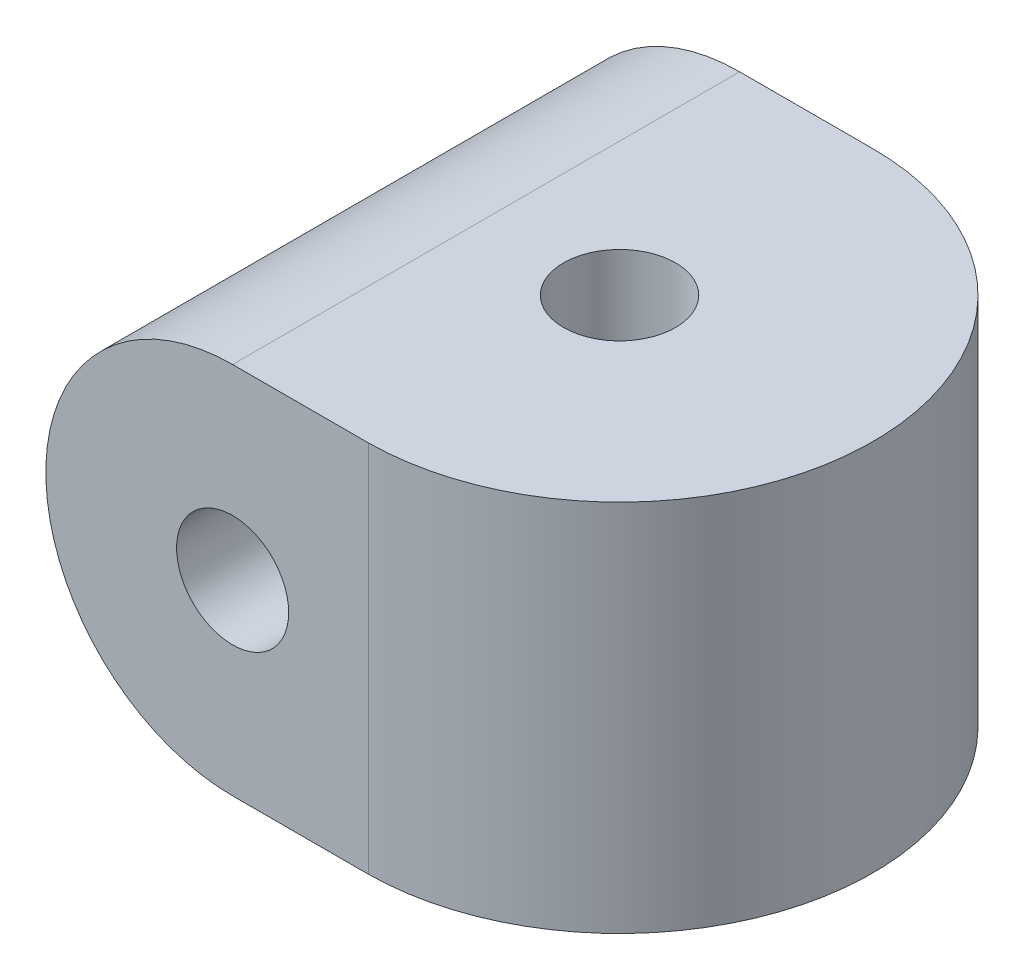
SolidWorks part; units mm, degrees
ref_plane "Alzado" through (0, 0, 0) normal (0, 0, 1) x (1, 0, 0)
ref_plane "Planta" through (0, 0, 0) normal (0, 1, 0) x (1, 0, 0)
ref_plane "Vista lateral" through (0, 0, 0) normal (1, 0, 0) x (0, 0, -1)
sketch "Croquis1" plane through (0, 0, 0) normal (0, 1, 0) x (1, 0, 0)
  line L0 (0, 9.5) -> (-15, 9.5)
  line L1 (-15, 9.5) -> (-15, -9.4996)
  line L2 (-15, -9.4996) -> (0.0848, -9.4996)
  line L3 (0, 0) -> (0, 50000) construction
  line L4 (-5, -17.8118) -> (-5, 49982.1882) construction
  circle A0 centre (0, 0) radius 9.5 construction
  circle A1 centre (0, 0) radius 2.1
  arc A2 (0, 9.5) -> (0.0848, -9.4996) centre (0, 0) cw
  dimension "D1" = 4.2
  dimension "D2" = 19
  dimension "D3" = 5
  dimension "D4" = 10
extrude "Saliente-Extruir1" add sketch "Croquis1" along normal mid plane 14
sketch "Croquis2" plane through (0, 0, 9.4996) normal (0, 0, 1) x (1, 0, 0)
  line L0 (0, 0) -> (-15, 0) construction
  circle A0 centre (-5, 0) radius 2.1
  dimension "D1" = 5
  dimension "D2" = 4.2
extrude "Cortar-Extruir1" cut sketch "Croquis2" against normal through all
sketch "Croquis3" plane through (0, 0, 9.4996) normal (0, 0, 1) x (1, 0, 0)
  line L0 (-15, 7) -> (0.0848, 7) construction
  line L1 (-15, -7) -> (0.0848, -7) construction
  line L2 (-5, 7) -> (-15, 7)
  line L3 (-15, 7) -> (-15, -7)
  line L4 (-15, -7) -> (-5, -7)
  arc A0 (-5, 7) -> (-5, -7) centre (-5, 0) ccw
extrude "Cortar-Extruir2" cut sketch "Croquis3" against normal through all
